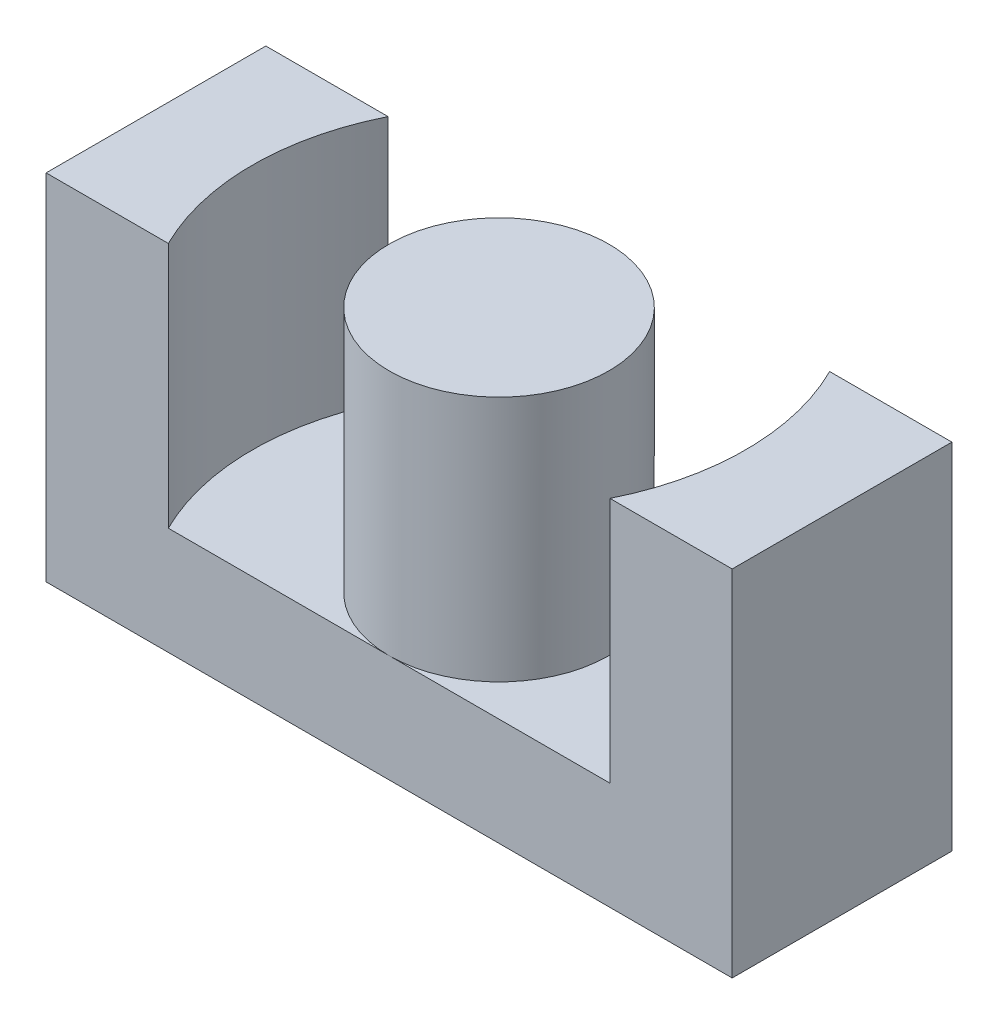
SolidWorks part; units mm, degrees
ref_plane "Plane1" through (0, 0, 0) normal (0, 0, 1) x (1, 0, 0)
ref_plane "Plane2" through (0, 0, 0) normal (0, 1, 0) x (1, 0, 0)
ref_plane "Plane3" through (0, 0, 0) normal (1, 0, 0) x (0, 0, -1)
sketch "Sketch1" plane through (0, 0, 0) normal (0, 1, 0) x (1, 0, 0)
  line L0 (0, 4.9) -> (0, -4.9) construction
  line L1 (-15.3, 4.9) -> (15.3, 4.9)
  line L2 (-15.3, 4.9) -> (-15.3, -4.9)
  line L3 (-15.3, -4.9) -> (15.3, -4.9)
  line L4 (15.3, 4.9) -> (15.3, -4.9)
  dimension "D1" = 30.6
  dimension "D2" = 9.8
extrude "Base-Extrude" add sketch "Sketch1" along normal blind 15.8
sketch "Sketch2" plane through (0, 15.8, 0) normal (0, 1, 0) x (-1, 0, 0)
  circle A0 centre (0, 0) radius 11
  circle A1 centre (0, 0) radius 4.9
  dimension "D1" = 22
  dimension "D2" = 9.8
extrude "Cut-Extrude1" cut sketch "Sketch2" against normal blind 11
